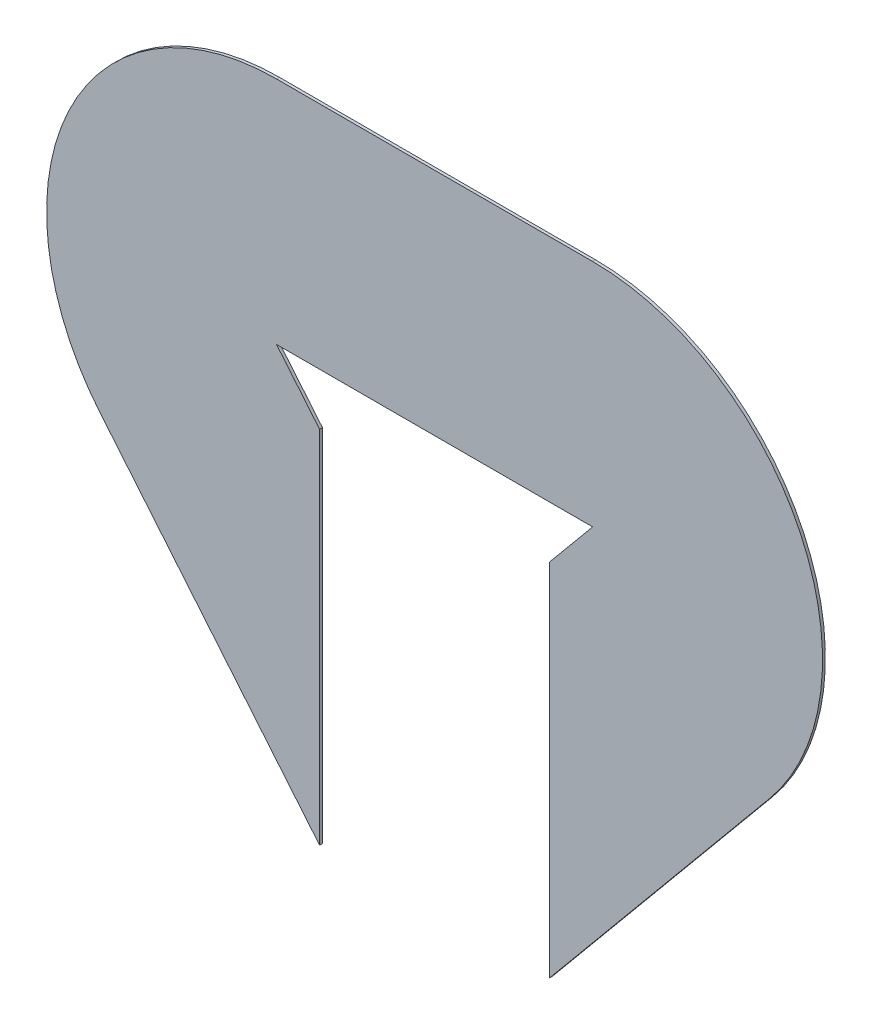
SolidWorks part; units mm, degrees
ref_plane "Front Plane" through (0, 0, 0) normal (0, 0, 1) x (1, 0, 0)
ref_plane "Top Plane" through (0, 0, 0) normal (0, 1, 0) x (1, 0, 0)
ref_plane "Right Plane" through (0, 0, 0) normal (1, 0, 0) x (0, 0, -1)
sketch "Sketch1" plane through (0, 0, 0) normal (0, 0, 1) x (1, 0, 0)
  line L0 (280.77, 169.165) -> (242.67, 123.2081)
  line L8 (1.37, 169.165) -> (39.47, 123.2081)
  line L11 (39.47, 169.165) -> (242.67, 169.165)
  line L13 (242.67, -195.1723) -> (242.67, 123.2081)
  line L20 (1.37, 169.165) -> (39.47, 169.165)
  line L21 (280.77, 169.165) -> (242.67, 169.165)
  line L31 (-155.0626, 39.4766) -> (39.47, -195.1723)
  line L33 (242.67, -195.1723) -> (437.2026, 39.4766)
  line L34 (1.37, 372.365) -> (280.77, 372.365)
  line L47 (39.47, -195.1723) -> (39.47, 123.2081)
  arc A2 (1.37, 372.365) -> (-155.0626, 39.4766) centre (1.37, 169.165) ccw
  arc A3 (280.77, 372.365) -> (437.2026, 39.4766) centre (280.77, 169.165) cw
  dimension "D5" = 304.8
  dimension "D11" = 59.6963
  dimension "D12" = 279.4
  dimension "D3" = 203.2
  dimension "D8" = 203.2
  dimension "D2" = 203.2
  dimension "D6" = 279.4
  dimension "D7" = 304.8
  dimension "D9" = 38.1
  dimension "D13" = 45.9569
extrude "Boss-Extrude2" add sketch "Sketch1" along normal blind 2.54
